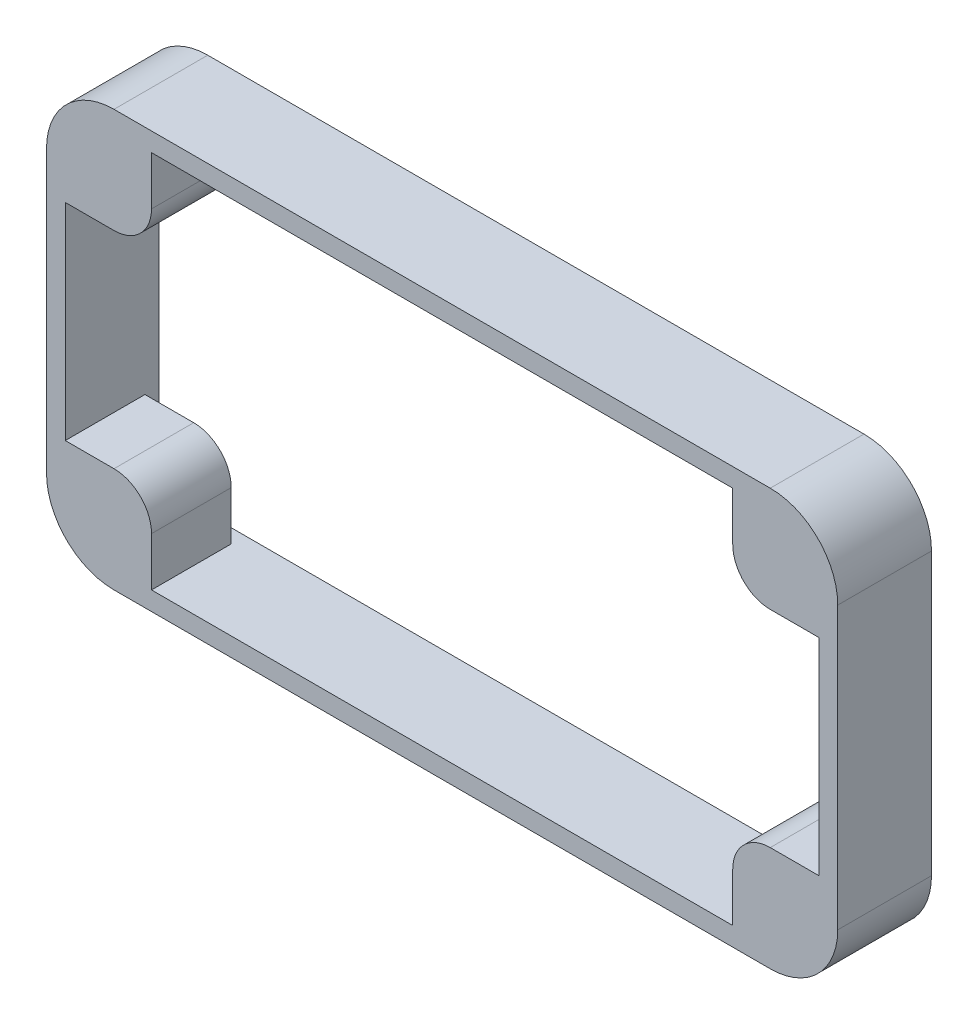
SolidWorks part; units mm, degrees
ref_plane "Спереди" through (0, 0, 0) normal (0, 0, 1) x (1, 0, 0)
ref_plane "Сверху" through (0, 0, 0) normal (0, 1, 0) x (1, 0, 0)
ref_plane "Справа" through (0, 0, 0) normal (1, 0, 0) x (0, 0, -1)
sketch "Эскиз1" plane through (0, 0, 0) normal (0, 0, 1) x (1, 0, 0)
  line L0 (-40.2, -15) -> (-40.2, 15)
  line L1 (-35, -15) -> (35, -15) construction
  line L2 (-35, -15) -> (-35, 15) construction
  line L3 (-35, 15) -> (35, 15) construction
  line L4 (35, -15) -> (35, 15) construction
  line L5 (-35, -15) -> (35, 15) construction
  line L6 (-35, 15) -> (35, -15) construction
  line L7 (-35, 20.2) -> (35, 20.2)
  line L8 (40.2, 15) -> (40.2, -15)
  line L9 (35, -20.2) -> (-35, -20.2)
  line L10 (-35, 22.2) -> (35, 22.2)
  line L11 (42.2, 15) -> (42.2, -15)
  line L12 (35, -22.2) -> (-35, -22.2)
  line L13 (-42.2, -15) -> (-42.2, 15)
  arc A0 (-35, 20.2) -> (-40.2, 15) centre (-35, 15) ccw
  arc A1 (35, 20.2) -> (40.2, 15) centre (35, 15) cw
  arc A2 (40.2, -15) -> (35, -20.2) centre (35, -15) cw
  arc A3 (-35, -20.2) -> (-40.2, -15) centre (-35, -15) cw
  arc A4 (35, 22.2) -> (42.2, 15) centre (35, 15) cw
  arc A5 (42.2, -15) -> (35, -22.2) centre (35, -15) cw
  arc A6 (-35, -22.2) -> (-42.2, -15) centre (-35, -15) cw
  arc A7 (-35, 22.2) -> (-42.2, 15) centre (-35, 15) ccw
  point P0 (0, 0)
  dimension "D3" = 5.2
  dimension "D1" = 30
  dimension "D2" = 70
  dimension "D4" = 2
extrude "Бобышка-Вытянуть1" add sketch "Эскиз1" along normal blind 10
sketch "Эскиз2" plane through (0, 0, 0) normal (0, 0, -1) x (-1, 0, 0)
  line L1 (31, 15) -> (31, 20.2)
  line L2 (-35, 20.2) -> (35, 20.2) construction
  line L3 (35, 11) -> (40.2, 11)
  line L4 (40.2, 15) -> (40.2, -15) construction
  line L5 (40.2, 11) -> (40.2, 15)
  line L6 (35, 20.2) -> (31, 20.2)
  line L7 (0, 35.8183) -> (0, -32.1968) construction
  line L8 (56.1858, 0) -> (-53.3656, 0) construction
  line L9 (-35, 20.2) -> (-31, 20.2)
  line L10 (-40.2, 11) -> (-40.2, 15)
  line L11 (-35, 11) -> (-40.2, 11)
  line L12 (-31, 15) -> (-31, 20.2)
  line L13 (-31, -15) -> (-31, -20.2)
  line L14 (-35, -11) -> (-40.2, -11)
  line L15 (-40.2, -11) -> (-40.2, -15)
  line L16 (-35, -20.2) -> (-31, -20.2)
  line L17 (35, -20.2) -> (31, -20.2)
  line L18 (40.2, -11) -> (40.2, -15)
  line L19 (35, -11) -> (40.2, -11)
  line L20 (31, -15) -> (31, -20.2)
  arc A0 (35, 11) -> (31, 15) centre (35, 15) cw
  arc A1 (40.2, 15) -> (35, 20.2) centre (35, 15) ccw construction
  arc A2 (40.2, 15) -> (35, 20.2) centre (35, 15) ccw
  arc A3 (-40.2, 15) -> (-35, 20.2) centre (-35, 15) cw
  arc A5 (-35, 11) -> (-31, 15) centre (-35, 15) ccw
  arc A6 (-35, -11) -> (-31, -15) centre (-35, -15) cw
  arc A7 (-40.2, -15) -> (-35, -20.2) centre (-35, -15) ccw
  arc A8 (40.2, -15) -> (35, -20.2) centre (35, -15) cw
  arc A9 (35, -11) -> (31, -15) centre (35, -15) ccw
  point P0 (35, 15)
  point P1 (-35, 15)
  point P3 (-35, -15)
  point P5 (35, -15)
  dimension "D1" = 4
extrude "Бобышка-Вытянуть2" add sketch "Эскиз2" against normal blind 8.5 from offset 1.5 offset against normal yes
sketch "Эскиз3" plane through (0, 0, 10) normal (0, 0, 1) x (1, 0, 0)
  line L1 (-30, -12.5) -> (30, -12.5)
  line L2 (-30, -12.5) -> (-30, 12.5)
  line L3 (-30, 12.5) -> (30, 12.5)
  line L4 (30, -12.5) -> (30, 12.5)
  line L5 (-30, -12.5) -> (30, 12.5) construction
  line L6 (-30, 12.5) -> (30, -12.5) construction
  point P0 (0, 0)
  dimension "D1" = 25
  dimension "D2" = 60
